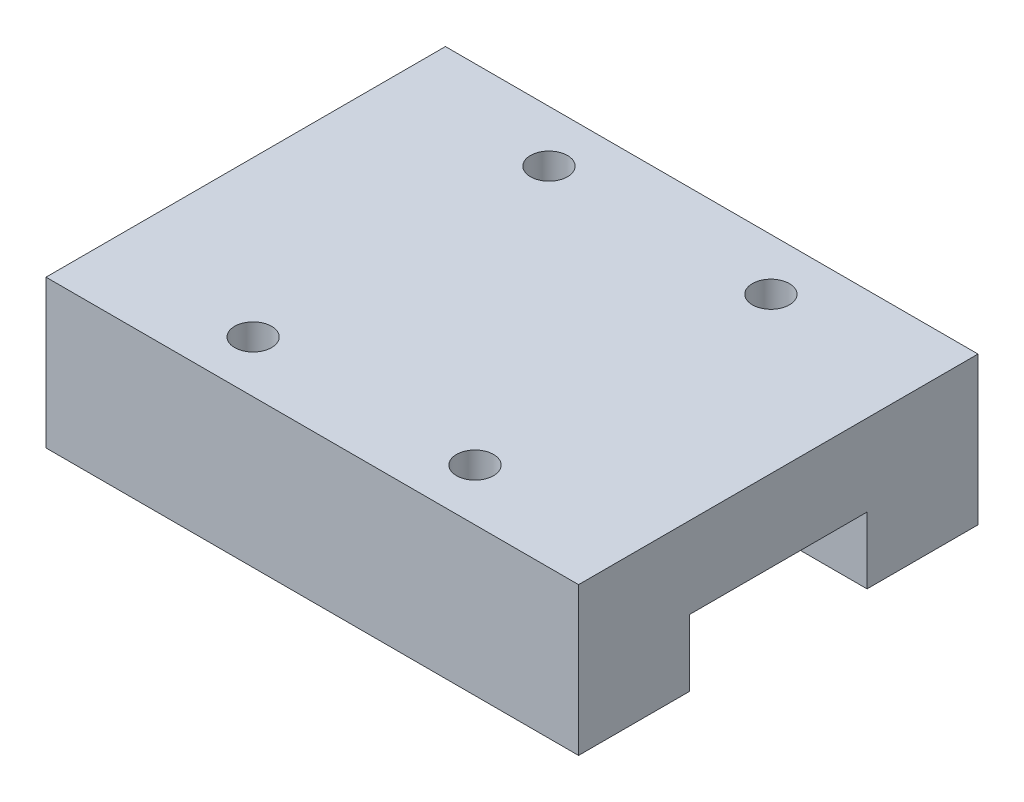
SolidWorks part; units mm, degrees
ref_plane "前视" through (0, 0, 0) normal (0, 0, 1) x (1, 0, 0)
ref_plane "上视" through (0, 0, 0) normal (0, 1, 0) x (1, 0, 0)
ref_plane "右视" through (0, 0, 0) normal (1, 0, 0) x (0, 0, -1)
sketch "草图1" plane through (0, 0, 0) normal (1, 0, 0) x (0, 0, -1)
  line L0 (6, -10) -> (13.5, -10)
  line L1 (-13.5, 0) -> (13.5, 0)
  line L2 (-13.5, 0) -> (-13.5, -10)
  line L3 (-13.5, -10) -> (-6, -10)
  line L4 (13.5, 0) -> (13.5, -10)
  line L5 (-6, -5.5) -> (6, -5.5)
  line L6 (-6, -5.5) -> (-6, -10)
  line L8 (6, -5.5) -> (6, -10)
  dimension "D1" = 13.5
  dimension "D2" = 13.5
  dimension "D3" = 10
  dimension "D4" = 5.5
  dimension "D5" = 6
  dimension "D6" = 6
extrude "拉伸1" add sketch "草图1" along normal blind 36
sketch "草图2" plane through (0, 0, 0) normal (0, 1, 0) x (1, 0, 0)
  point P0 (10.5, 10)
  point P1 (25.5, 10)
  point P3 (10.5, -10)
  point P4 (25.5, -10)
  dimension "D1" = 10
  dimension "D2" = 10.5
  dimension "D3" = 15
  dimension "D4" = 10
  dimension "D5" = 15
  dimension "D6" = 10.5
hole_wizard "M3 螺纹孔1" positions "3D草图1" profile "草图3" tap size "M3" standard "ISO"
sketch3d "3D草图1"
  point P0 (10.5, 0, 10)
  point P3 (25.5, 0, 10)
  point P6 (25.5, 0, -10)
  point P9 (10.5, 0, -10)
sketch "草图3" plane through (10.5, 0, 10) normal (1, 0, 0) x (0, 0, 1)
  line L0 (0, 0) -> (0, 9.2511)
  line L1 (0, 9.2511) -> (1.25, 8.5)
  line L2 (1.25, 8.5) -> (1.25, 0)
  line L5 (1.25, 0) -> (0, 0)
  line L10 (0, 9.2511) -> (-1.25, 8.5) construction
  line L11 (0, -6.35) -> (0, 107.95) construction
  dimension "螺纹孔钻头直径" = 2.5
  dimension "螺纹孔钻头深度" = 8.5
  dimension "导头角度" = 118
cosmetic thread "孔螺蚊线1" parameters "D1"=6, "D2"=3
cosmetic thread "孔螺蚊线2" parameters "D1"=6, "D2"=3
cosmetic thread "孔螺蚊线3" parameters "D1"=6, "D2"=3
cosmetic thread "孔螺蚊线4" parameters "D1"=6, "D2"=3
